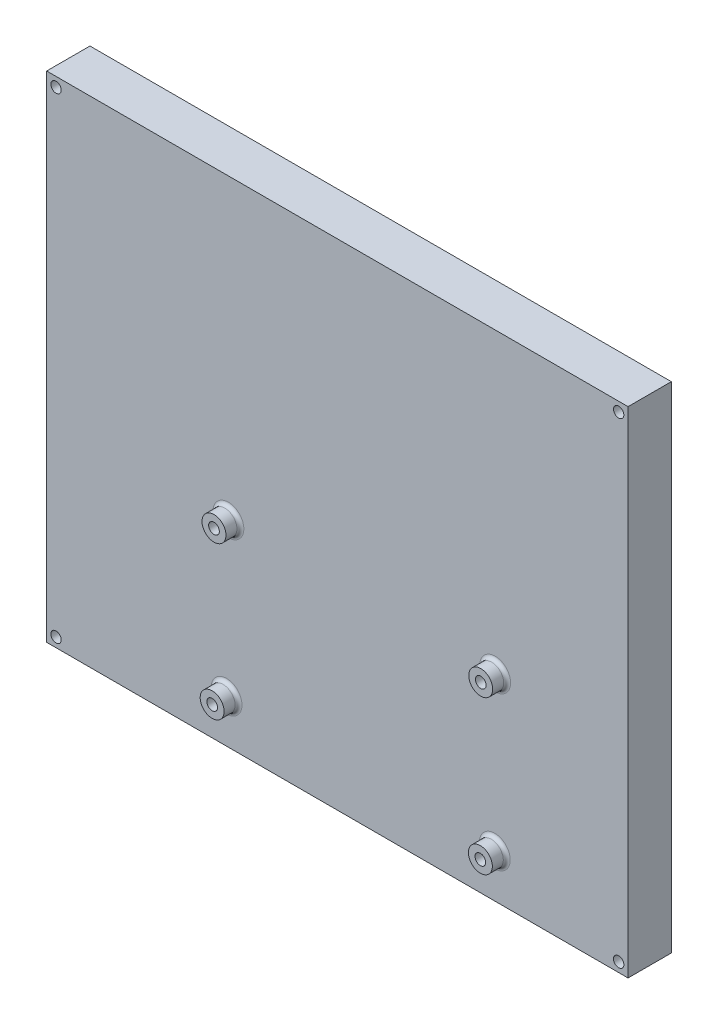
SolidWorks part; units mm, degrees
ref_plane "Front Plane" through (0, 0, 0) normal (0, 0, 1) x (1, 0, 0)
ref_plane "Top Plane" through (0, 0, 0) normal (0, 1, 0) x (1, 0, 0)
ref_plane "Right Plane" through (0, 0, 0) normal (1, 0, 0) x (0, 0, -1)
sketch "Sketch1" plane through (0, 0, 0) normal (0, 0, 1) x (1, 0, 0)
  line L1 (-100.75, 85.75) -> (100.75, 85.75)
  line L2 (-100.75, 85.75) -> (-100.75, -85.75)
  line L3 (-100.75, -85.75) -> (100.75, -85.75)
  line L4 (100.75, 85.75) -> (100.75, -85.75)
  line L5 (-100.75, 85.75) -> (100.75, -85.75) construction
  line L6 (-100.75, -85.75) -> (100.75, 85.75) construction
  point P0 (0, 0)
  dimension "D1" = 201.5
  dimension "D2" = 171.5
extrude "Main Body" add sketch "Sketch1" along normal blind 15
sketch "Sketch2" plane through (0, 0, 15) normal (0, 0, 1) x (1, 0, 0)
  line L1 (-95, 80) -> (95, 80)
  line L2 (-95, 80) -> (-95, -80)
  line L3 (-95, -80) -> (95, -80)
  line L4 (95, 80) -> (95, -80)
  line L5 (-95, 80) -> (95, -80) construction
  line L6 (-95, -80) -> (95, 80) construction
  circle A0 centre (-97.5, 82.5) radius 1.8
  circle A1 centre (97.5, 82.5) radius 1.8
  circle A2 centre (97.5, -82.5) radius 1.8
  circle A3 centre (-97.5, -82.5) radius 1.8
  point P0 (0, 0)
  dimension "D3" = 3.6
  dimension "D4" = 3.6
  dimension "D5" = 3.6
  dimension "D6" = 3.6
  dimension "D1" = 190
  dimension "D2" = 160
  dimension "D7" = 2.5
  dimension "D8" = 2.5
  dimension "D9" = 2.5
  dimension "D10" = 2.5
  dimension "D11" = 2.5
  dimension "D12" = 2.5
  dimension "D13" = 2.5
  dimension "D14" = 2.5
extrude "Screw Holes" cut sketch "Sketch2" against normal blind 15 contours A1 | A0 | A3 | A2
sketch "Sketch3" plane through (0, 0, 15) normal (0, 0, 1) x (1, 0, 0)
  circle A0 centre (-37.764, -17.5345) radius 1.85
  circle A1 centre (54.692, -17.5345) radius 1.85
  circle A2 centre (54.565, -70.7475) radius 1.85
  circle A3 centre (-38.399, -70.7475) radius 1.85
  dimension "D1" = 3.7
  dimension "D2" = 3.7
  dimension "D3" = 3.7
  dimension "D4" = 3.7
extrude "PCB Screw Area" add sketch "Sketch3" along normal blind 5 thin
sketch "Sketch4" plane through (0, 0, 0) normal (0, 0, -1) x (-1, 0, 0)
  line L1 (-90, 75) -> (90, 75)
  line L2 (-90, 75) -> (-90, -75)
  line L3 (-90, -75) -> (90, -75)
  line L4 (90, 75) -> (90, -75)
  line L5 (-90, 75) -> (90, -75) construction
  line L6 (-90, -75) -> (90, 75) construction
  point P0 (0, 0)
  dimension "D1" = 180
  dimension "D2" = 150
extrude "Main Cut" cut sketch "Sketch4" against normal blind 12
fillet "Fillet3" radius 1.2 4 edges at (-34.249, -70.7475, 15) (58.715, -70.7475, 15) (58.842, -17.5345, 15) (-33.614, -17.5345, 15)
sketch "Sketch6" plane through (0, 0, 15) normal (0, 0, 1) x (1, 0, 0)
  circle A0 centre (-37.764, -17.5345) radius 1.85
  circle A1 centre (-38.399, -70.7475) radius 1.85
  circle A2 centre (54.565, -70.7475) radius 1.85
  circle A3 centre (54.692, -17.5345) radius 1.85
  dimension "D1" = 3.7
  dimension "D2" = 3.7
  dimension "D3" = 3.7
  dimension "D4" = 3.7
extrude "PCB Screw Holes" cut sketch "Sketch6" against normal blind 2
